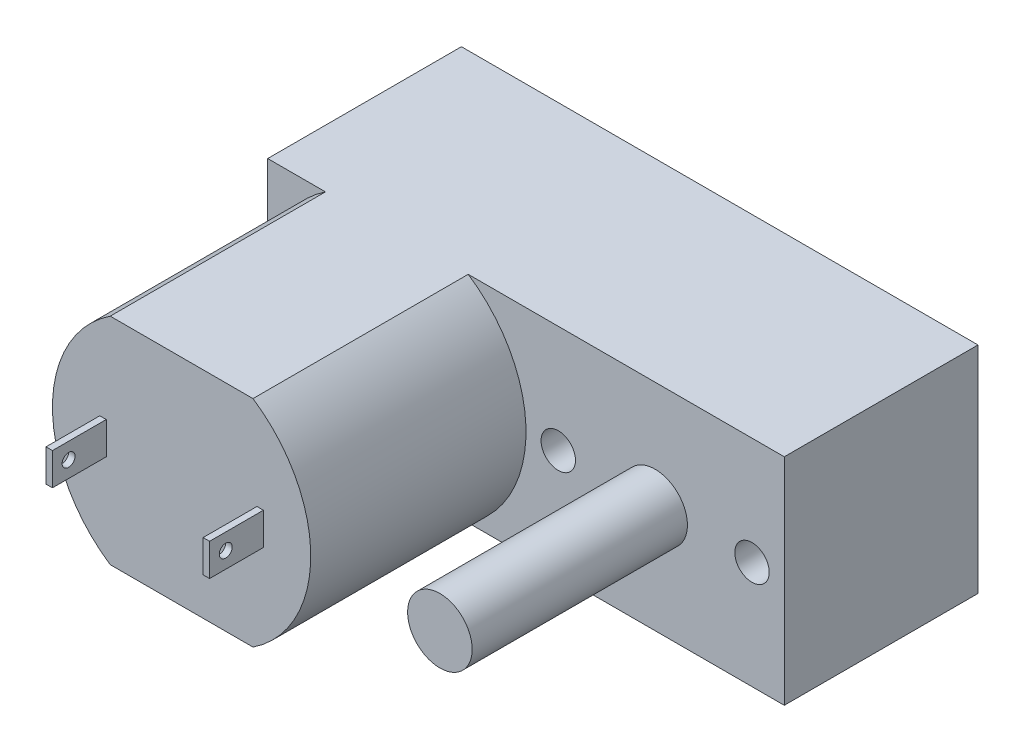
SolidWorks part; units mm, degrees
ref_plane "Front Plane" through (0, 0, 0) normal (0, 0, 1) x (1, 0, 0)
ref_plane "Top Plane" through (0, 0, 0) normal (0, 1, 0) x (1, 0, 0)
ref_plane "Right Plane" through (0, 0, 0) normal (1, 0, 0) x (0, 0, -1)
sketch "草图1" plane through (0, 0, 0) normal (0, 0, 1) x (1, 0, 0)
  line L1 (0, 0) -> (12, 0)
  line L2 (0, 0) -> (0, 10)
  line L3 (0, 10) -> (12, 10)
  line L4 (12, 0) -> (12, 10)
extrude "凸台-拉伸1" add sketch "草图1" along normal blind 19
sketch "草图2" plane through (0, 0, 0) normal (0, 0, 1) x (1, 0, 0)
  circle A0 centre (6, 5) radius 6
extrude "切除-拉伸1" cut sketch "草图2" along normal blind 19 flip side to cut
sketch "草图3" plane through (0, 0, 0) normal (0, 0, 1) x (1, 0, 0)
  line L1 (0, 0) -> (24, 0)
  line L2 (0, 0) -> (0, 10)
  line L3 (0, 10) -> (24, 10)
  line L4 (24, 0) -> (24, 10)
extrude "凸台-拉伸2" add sketch "草图3" along normal blind 9
sketch "草图4" plane through (0, 0, 9) normal (0, 0, 1) x (1, 0, 0)
  circle A0 centre (18, 5) radius 1.5
extrude "凸台-拉伸3" add sketch "草图4" along normal blind 10
sketch "草图9" plane through (0, 0, 9) normal (0, 0, 1) x (1, 0, 0)
  circle A0 centre (13.5, 5) radius 0.8
  circle A1 centre (22.5, 5) radius 0.8
extrude "切除-拉伸2" cut sketch "草图9" against normal blind 3
sketch "草图10" plane through (0, 0, 19) normal (0, 0, 1) x (1, 0, 0)
  line L1 (2.5, 5.75) -> (2.2, 5.75)
  line L2 (2.5, 5.75) -> (2.5, 4.25)
  line L3 (2.5, 4.25) -> (2.2, 4.25)
  line L4 (2.2, 5.75) -> (2.2, 4.25)
  line L5 (9.5, 4.25) -> (9.8, 4.25)
  line L6 (9.5, 4.25) -> (9.5, 5.75)
  line L7 (9.5, 5.75) -> (9.8, 5.75)
  line L8 (9.8, 4.25) -> (9.8, 5.75)
extrude "凸台-拉伸5" add sketch "草图10" along normal blind 2.5
sketch "草图12" plane through (2.2, 0, 0) normal (-1, 0, 0) x (0, 0, 1)
  circle A0 centre (20.75, 5) radius 0.3
extrude "切除-拉伸3" cut sketch "草图12" against normal blind 7.6
